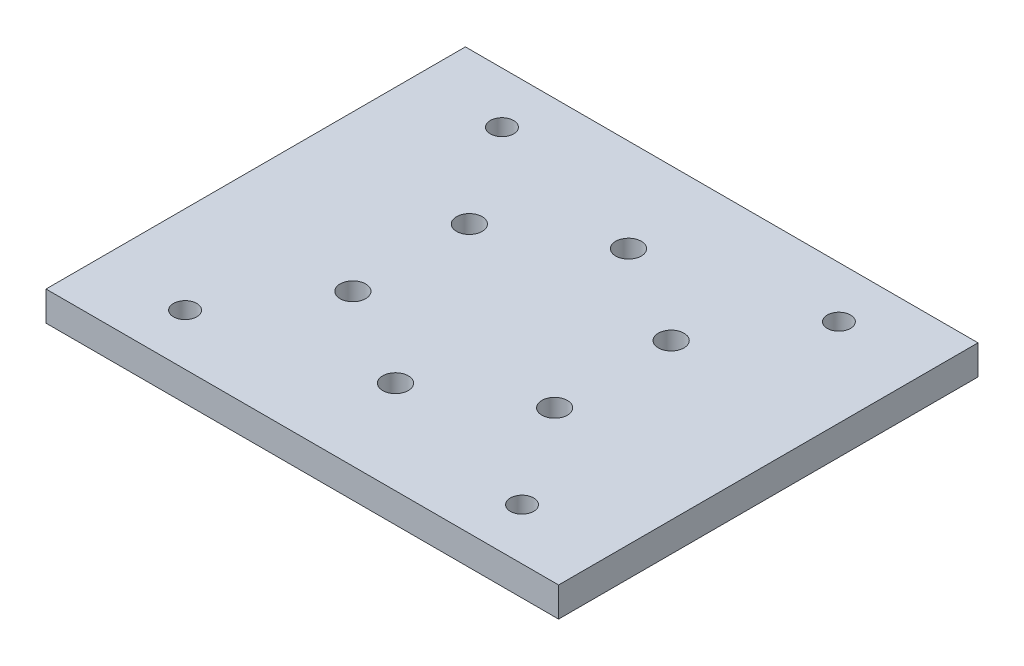
SolidWorks part; units mm, degrees
material "6061 Alloy"
ref_plane "Front Plane" through (0, 0, 0) normal (0, 0, 1) x (1, 0, 0)
ref_plane "Top Plane" through (0, 0, 0) normal (0, 1, 0) x (1, 0, 0)
ref_plane "Right Plane" through (0, 0, 0) normal (1, 0, 0) x (0, 0, -1)
sketch "Sketch2" plane through (0, 0, 0) normal (0, 1, 0) x (1, 0, 0)
  line L0 (0, 0) -> (0, 90)
  line L1 (0, 90) -> (110, 90)
  line L2 (110, 90) -> (110, 0)
  line L3 (110, 0) -> (0, 0)
  dimension "D1" = 110
  dimension "D2" = 90
extrude "Boss-Extrude1" add sketch "Sketch2" along normal blind 6.35
sketch "Sketch3" plane through (0, 6.35, 0) normal (0, 1, 0) x (1, 0, 0)
  line L1 (110, 90) -> (0, 90) construction
  line L2 (0, 0) -> (110, 0) construction
  line L4 (55, 90) -> (55, 0) construction
  line L5 (0, 45) -> (55, 45) construction
  line L6 (55, 45) -> (110, 45) construction
  line L7 (0, 90) -> (0, 0) construction
  circle A0 centre (18.85, 79) radius 2.5
  circle A1 centre (18.85, 11) radius 2.5
  circle A2 centre (91.15, 11) radius 2.5
  circle A3 centre (91.15, 79) radius 2.5
  dimension "D4" = 5
  dimension "D3" = 11
  dimension "D2" = 18.85
extrude "Mounting Holes" cut sketch "Sketch3" against normal through all
sketch "Sketch4" plane through (0, 6.35, 0) normal (0, 1, 0) x (1, 0, 0)
  line L0 (18.85, 79) -> (91.15, 11) construction
  circle A0 centre (55, 45) radius 25 construction
  circle A1 centre (55, 70) radius 2.75
  circle A2 centre (76.6506, 57.5) radius 2.75
  circle A3 centre (76.6506, 32.5) radius 2.75
  circle A4 centre (55, 20) radius 2.75
  circle A5 centre (33.3494, 32.5) radius 2.75
  circle A6 centre (33.3494, 57.5) radius 2.75
  point P20 (55, 45)
  dimension "D1" = 50
  dimension "D2" = 5.5
  dimension "D3" = 6
extrude "Cut-Extrude1" cut sketch "Sketch4" against normal through all
sketch "Sketch5" plane through (0, 6.35, 0) normal (0, 1, 0) x (1, 0, 0)
  circle A0 centre (55, 45) radius 25 construction
  circle A1 centre (55, 20) radius 2.75 construction
  circle A2 centre (55, 20) radius 2.75 construction
  circle A3 centre (33.3494, 32.5) radius 2.75 construction
  circle A4 centre (33.3494, 32.5) radius 2.75 construction
  circle A5 centre (33.3494, 57.5) radius 2.75 construction
  circle A6 centre (33.3494, 57.5) radius 2.75 construction
equation "\"L1L\"=500"
equation "\"L1Thick\"=6.35"
equation "\"Harm-Drive-Outer\"=74.5"
equation "\"L1-Spacing\"=100"
equation "\"L-Bracket-HoleToWall\"=12.5"
equation "\"D3@Sketch3\"=\"L-Bracket-HoleToSide\""
equation "\"L-Bracket-HoleToSide\"=11"
equation "\"Bracket-Hole-D\"=6.8"
equation "\"L1-Spacing\"=115.65"
equation "\"D2@Sketch3\"=\"L-Bracket-HoleToWall\"+\"L1Thick\""
